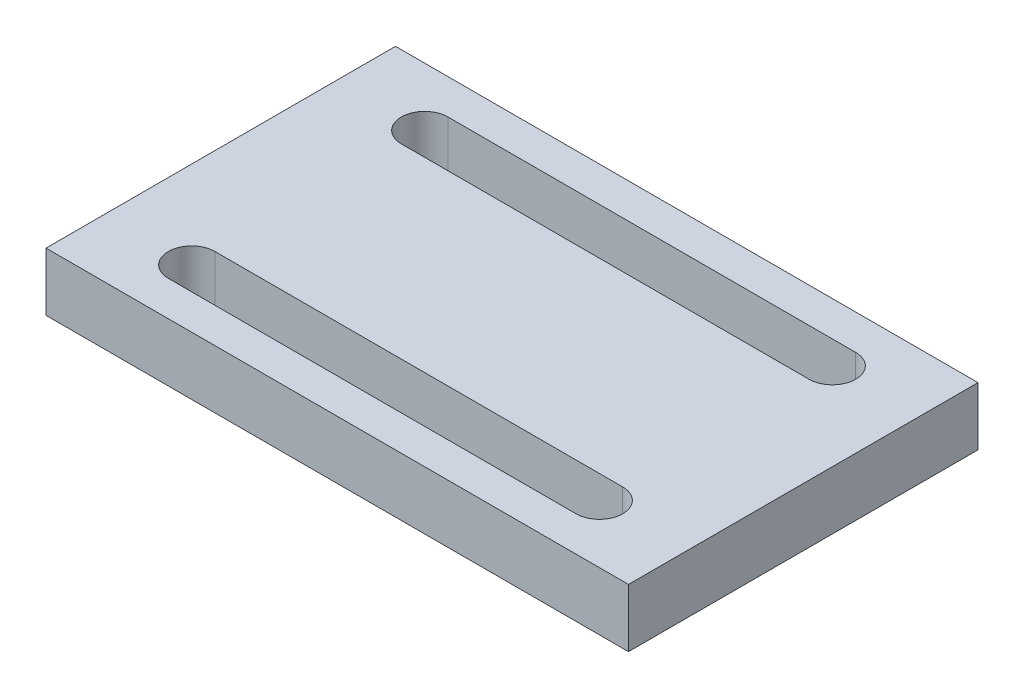
SolidWorks part; units mm, degrees
ref_plane "Front Plane" through (0, 0, 0) normal (0, 0, 1) x (1, 0, 0)
ref_plane "Top Plane" through (0, 0, 0) normal (0, 1, 0) x (1, 0, 0)
ref_plane "Right Plane" through (0, 0, 0) normal (1, 0, 0) x (0, 0, -1)
sketch "Sketch1" plane through (0, 0, 0) normal (0, 1, 0) x (1, 0, 0)
  line L0 (0, 0) -> (50, 0)
  line L1 (50, 0) -> (50, 30)
  line L2 (50, 30) -> (0, 30)
  line L3 (0, 30) -> (0, 0)
  line L4 (7.5, 27) -> (42.5, 27)
  line L5 (42.5, 23) -> (7.5, 23)
  line L6 (0, 15) -> (50, 15) construction
  line L7 (42.5, 7) -> (7.5, 7)
  line L8 (7.5, 3) -> (42.5, 3)
  arc A1 (42.5, 27) -> (42.5, 23) centre (42.5, 25) cw
  arc A2 (7.5, 23) -> (7.5, 27) centre (7.5, 25) cw
  arc A3 (7.5, 7) -> (7.5, 3) centre (7.5, 5) ccw
  arc A4 (42.5, 3) -> (42.5, 7) centre (42.5, 5) ccw
  point P11 (25, 23)
  point P12 (25, 0)
  point P21 (25, 7)
  dimension "D3" = 4
  dimension "D1" = 50
  dimension "D2" = 30
  dimension "D4" = 35
  dimension "D5" = 5
extrude "Boss-Extrude1" add sketch "Sketch1" along normal blind 5
